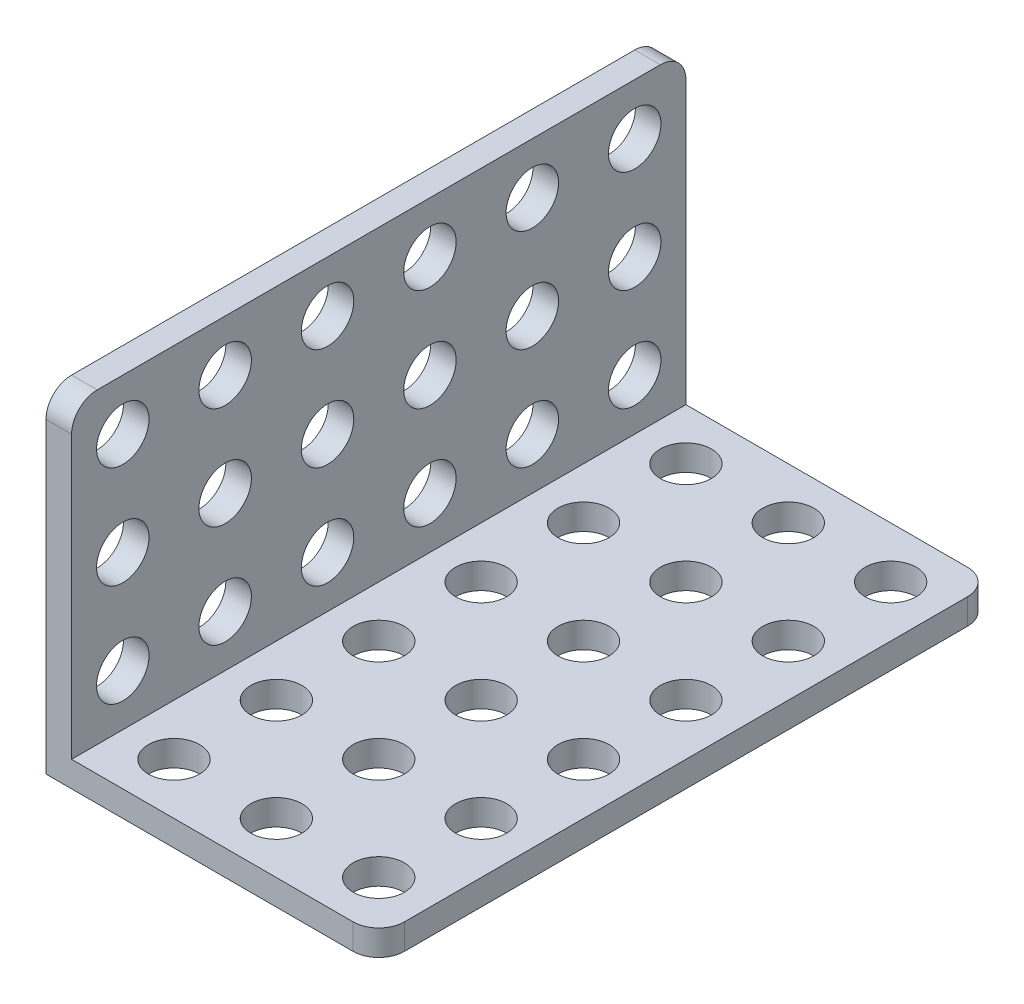
SolidWorks part; units mm, degrees
ref_plane "Front Plane" through (0, 0, 0) normal (0, 0, 1) x (1, 0, 0)
ref_plane "Top Plane" through (0, 0, 0) normal (0, 1, 0) x (1, 0, 0)
ref_plane "Right Plane" through (0, 0, 0) normal (1, 0, 0) x (0, 0, -1)
sketch "Sketch1" plane through (0, 0, 0) normal (0, 0, 1) x (1, 0, 0)
  line L0 (0, 0) -> (0, 26)
  line L1 (0, 26) -> (2, 26)
  line L2 (2, 26) -> (2, 2)
  line L3 (2, 2) -> (26, 2)
  line L4 (26, 2) -> (26, 0)
  line L5 (26, 0) -> (0, 0)
  dimension "D1" = 26
  dimension "D2" = 26
  dimension "D3" = 2
  dimension "D4" = 2
extrude "Boss-Extrude1" add sketch "Sketch1" along normal blind 48
sketch "Sketch2" plane through (2, 0, 0) normal (1, 0, 0) x (0, 0, -1)
  line L0 (-48, 26) -> (0, 26) construction
  line L2 (-48, 2) -> (-48, 26) construction
  circle A0 centre (-44, 22) radius 2.05
  dimension "D1" = 4.1
  dimension "D2" = 4
  dimension "D3" = 4
extrude "Cut-Extrude1" cut sketch "Sketch2" against normal through all
pattern_linear "LPattern1" count 6 spacing 8 along (0, 0, -1) count 3 spacing 8 along (0, -1, 0) of "Cut-Extrude1"
sketch "Sketch3" plane through (0, 2, 0) normal (0, 1, 0) x (1, 0, 0)
  line L0 (26, 0) -> (2, 0) construction
  line L1 (26, -48) -> (26, 0) construction
  circle A0 centre (22, -4) radius 2
  dimension "D1" = 4
  dimension "D2" = 4
  dimension "D3" = 4
extrude "Cut-Extrude2" cut sketch "Sketch3" against normal through all
pattern_linear "LPattern2" count 6 spacing 8 along (0, 0, 1) count 3 spacing 8 along (-1, 0, 0) of "Cut-Extrude2"
fillet "Fillet1" radius 2 4 edges at (1, 26, 0) (1, 26, 48) (26, 1, 48) (26, 1, 0)
